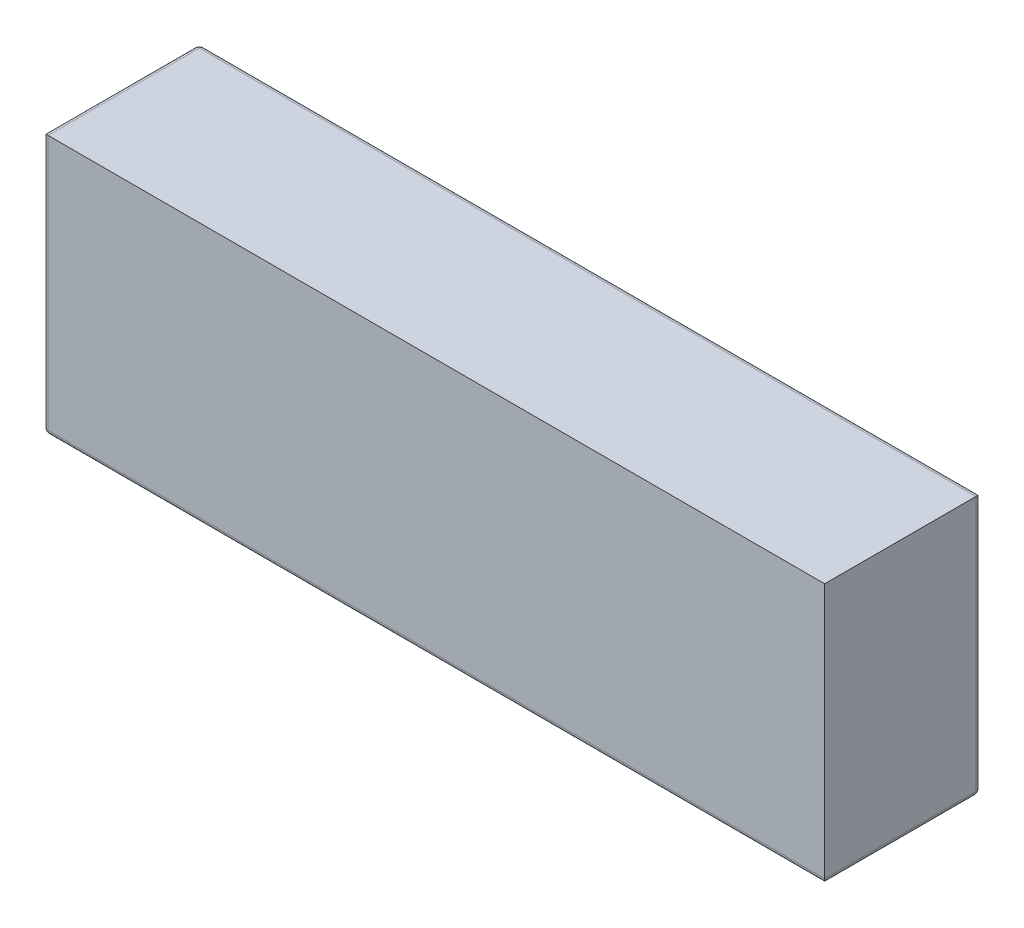
SolidWorks part; units mm, degrees
material "Maple"
ref_plane "Front Plane" through (0, 0, 0) normal (0, 0, 1) x (1, 0, 0)
ref_plane "Top Plane" through (0, 0, 0) normal (0, 1, 0) x (1, 0, 0)
ref_plane "Right Plane" through (0, 0, 0) normal (1, 0, 0) x (0, 0, -1)
sketch "Sketch1" plane through (0, 0, 0) normal (0, 0, 1) x (1, 0, 0)
  line L1 (-75, 25) -> (75, 25)
  line L2 (-75, 25) -> (-75, -25)
  line L3 (-75, -25) -> (75, -25)
  line L4 (75, 25) -> (75, -25)
  line L5 (-75, 25) -> (75, -25) construction
  line L6 (-75, -25) -> (75, 25) construction
  point P0 (0, 0)
  dimension "D1" = 50
  dimension "D2" = 150
extrude "Boss-Extrude1" add sketch "Sketch1" along normal blind 28
sketch "Sketch3" plane through (0, 0, 28) normal (0, 0, 1) x (1, 0, 0)
  line L1 (-75, 25) -> (75, 25)
  line L2 (-75, 25) -> (-75, -25)
  line L3 (-75, -25) -> (75, -25)
  line L4 (75, 25) -> (75, -25)
  line L5 (-75, 25) -> (75, -25) construction
  line L6 (-75, -25) -> (75, 25) construction
  point P0 (0, 0)
extrude "Boss-Extrude2" add sketch "Sketch3" along normal blind 1
sketch "Sketch4" plane through (0, 0, 0) normal (0, 0, -1) x (-1, 0, 0)
  line L1 (-75, 25) -> (75, 25)
  line L2 (-75, 25) -> (-75, -25)
  line L3 (-75, -25) -> (75, -25)
  line L4 (75, 25) -> (75, -25)
  line L5 (-75, 25) -> (75, -25) construction
  line L6 (-75, -25) -> (75, 25) construction
  point P0 (0, 0)
extrude "Boss-Extrude3" add sketch "Sketch4" along normal blind 1
fillet "Fillet1" radius 1 9 edges at (-75, 25, 14) (-75, -25, 14) (75, -25, 14) (0, -25, 29) (-75, 0, 29) (0, -25, -1) (75, 0, -1) (0, 25, -1) (-75, 0, -1)
sketch "Sketch5" plane through (0, 0, -1) normal (0, 0, -1) x (-1, 0, 0)
  line L0 (-92.6765, 14.1347) -> (-92.6765, 169.4681) construction
sketch "Sketch6" plane through (0, 0, 29) normal (0, 0, 1) x (1, 0, 0)
  line L0 (13.3076, 93.2758) -> (166.641, 93.2758) construction
sketch "Sketch7" plane through (0, 0, -1) normal (0, 0, -1) x (-1, 0, 0)
  line L0 (-0.5, 25) -> (-0.5, -25)
  line L1 (-75, 25) -> (74, 25) construction
  line L2 (74, -25) -> (-74, -25) construction
  line L4 (-25.5, 25) -> (24.5, 25)
  line L5 (-25.5, 25) -> (-25.5, -25)
  line L6 (-25.5, -25) -> (24.5, -25)
  line L7 (24.5, 25) -> (24.5, -25)
  line L8 (-25.5, 25) -> (24.5, -25) construction
  line L9 (-25.5, -25) -> (24.5, 25) construction
  point P6 (-0.5, 0)
  dimension "D1" = 50
